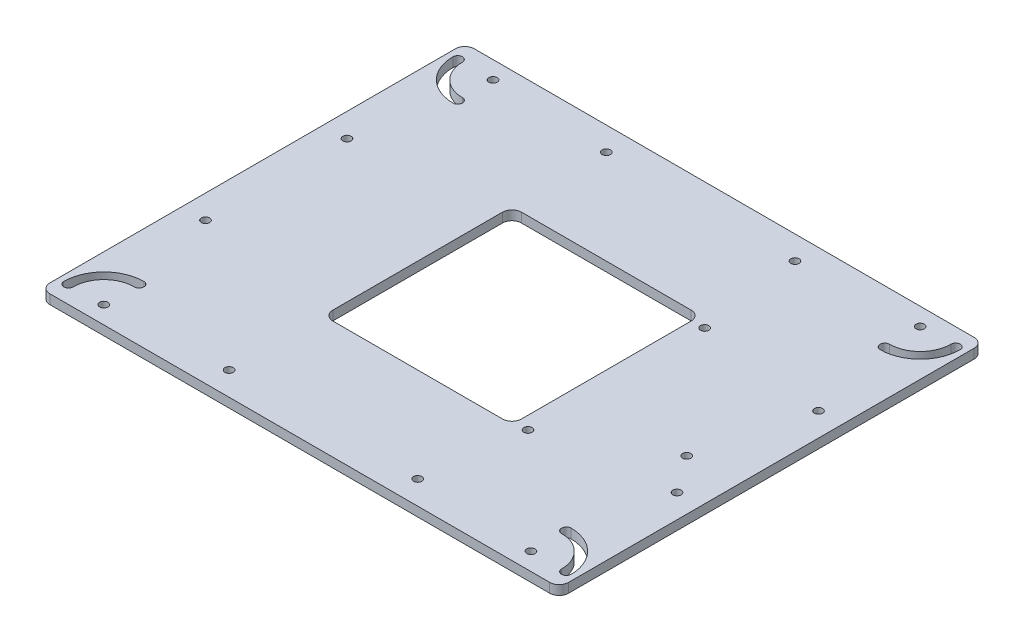
SolidWorks part; units mm, degrees
ref_plane "前视基准面" through (0, 0, 0) normal (0, 0, 1) x (1, 0, 0)
ref_plane "上视基准面" through (0, 0, 0) normal (0, 1, 0) x (1, 0, 0)
ref_plane "右视基准面" through (0, 0, 0) normal (1, 0, 0) x (0, 0, -1)
sketch "草图1" plane through (0, 0, 0) normal (0, 1, 0) x (1, 0, 0)
  line L1 (-110, -90) -> (110, -90)
  line L2 (-110, -90) -> (-110, 90)
  line L3 (-110, 90) -> (110, 90)
  line L4 (110, -90) -> (110, 90)
  line L5 (-110, -90) -> (110, 90) construction
  line L6 (-110, 90) -> (110, -90) construction
  point P0 (0, 0)
  dimension "D1" = 220
  dimension "D2" = 180
extrude "凸台-拉伸1" add sketch "草图1" along normal blind 4
sketch "草图2" plane through (0, 4, 0) normal (0, 1, 0) x (1, 0, 0)
  line L4 (110, -90) -> (110, 90)
  line L5 (110, 90) -> (-110, 90)
  line L6 (-110, 90) -> (-110, -90)
  line L7 (-110, -90) -> (110, -90)
  line L8 (110, -90) -> (110, 90)
  line L9 (110, 90) -> (-110, 90)
  line L10 (-110, 90) -> (-110, -90)
  line L11 (-110, -90) -> (110, -90)
  line L16 (-40, 40) -> (-40, -40)
  line L17 (-40, -40) -> (40, -40)
  line L18 (40, -40) -> (40, 40)
  line L19 (40, 40) -> (-40, 40)
  line L20 (-40, 40) -> (-40, -40)
  line L21 (-40, -40) -> (40, -40)
  line L22 (40, -40) -> (40, 40)
  line L23 (40, 40) -> (-40, 40)
  dimension "D1" = 0
  dimension "D2" = 10
extrude "切除-拉伸1" cut sketch "草图2" against normal blind 4 contours L20 L21 L22 L23
sketch "草图3" plane through (0, 0, 0) normal (0, -1, 0) x (-1, 0, 0)
  line L0 (123.6855, 0) -> (-123.4665, 0) construction
  line L1 (0, -98.0292) -> (0, 106.8372) construction
  circle A0 centre (90.5847, 82.5452) radius 1.75
  circle A1 centre (-90.5847, 82.5452) radius 1.75
  circle A2 centre (-90.5847, -82.5452) radius 1.75
  circle A3 centre (90.5847, -82.5452) radius 1.75
  arc A5 (90.5847, 65.5452) -> (107.5847, 82.5452) centre (90.5847, 82.5452) ccw
  arc A6 (90.5847, 69.5452) -> (103.5847, 82.5452) centre (90.5847, 82.5452) ccw
  arc A8 (107.5847, 82.5452) -> (103.5847, 82.5452) centre (105.5847, 82.5452) ccw
  arc A9 (90.5847, 69.5452) -> (90.5847, 65.5452) centre (90.5847, 67.5452) ccw
  arc A10 (90.5847, -69.5452) -> (90.5847, -65.5452) centre (90.5847, -67.5452) cw
  arc A11 (107.5847, -82.5452) -> (103.5847, -82.5452) centre (105.5847, -82.5452) cw
  arc A12 (90.5847, -69.5452) -> (103.5847, -82.5452) centre (90.5847, -82.5452) cw
  arc A13 (90.5847, -65.5452) -> (107.5847, -82.5452) centre (90.5847, -82.5452) cw
  circle A14 centre (90.5847, -82.5452) radius 1.75
  circle A15 centre (-90.5847, -82.5452) radius 1.75
  arc A16 (-90.5847, -65.5452) -> (-107.5847, -82.5452) centre (-90.5847, -82.5452) ccw
  arc A17 (-90.5847, -69.5452) -> (-103.5847, -82.5452) centre (-90.5847, -82.5452) ccw
  arc A18 (-107.5847, -82.5452) -> (-103.5847, -82.5452) centre (-105.5847, -82.5452) ccw
  arc A19 (-90.5847, -69.5452) -> (-90.5847, -65.5452) centre (-90.5847, -67.5452) ccw
  arc A20 (-90.5847, 69.5452) -> (-90.5847, 65.5452) centre (-90.5847, 67.5452) cw
  arc A21 (-107.5847, 82.5452) -> (-103.5847, 82.5452) centre (-105.5847, 82.5452) cw
  arc A22 (-90.5847, 69.5452) -> (-103.5847, 82.5452) centre (-90.5847, 82.5452) cw
  arc A23 (-90.5847, 65.5452) -> (-107.5847, 82.5452) centre (-90.5847, 82.5452) cw
  circle A24 centre (-90.5847, -82.5452) radius 1.75
  circle A25 centre (-90.5847, 82.5452) radius 1.75
  point P46 (0, 0)
extrude "切除-拉伸2" cut sketch "草图3" against normal blind 4 contours A6 A9 A5 A8 | A0 | A17 A19 A16 A18 | A2 | A23 A20 A22 A21 | A1 | A12 A11 A13 A10 | A3
sketch "草图5" plane through (0, 0, 0) normal (0, -1, 0) x (1, 0, 0)
  circle A0 centre (45.4012, 38.6263) radius 1.75
  circle A1 centre (88.5812, 14.4963) radius 1.75
  circle A2 centre (45.4012, -36.3037) radius 1.75
extrude "切除-拉伸3" cut sketch "草图5" against normal blind 4
sketch "草图6" plane through (0, 0, 0) normal (0, -1, 0) x (1, 0, 0)
  line L0 (-120.5811, 0) -> (119.4968, 0) construction
  line L1 (0, -99.411) -> (0, 101.0427) construction
  line L2 (110, -90) -> (-110, -90) construction
  line L3 (-110, -90) -> (-110, 90) construction
  circle A0 centre (-40, -80) radius 1.75
  circle A1 centre (-100, -30) radius 1.75
  circle A2 centre (40, -80) radius 1.75
  circle A3 centre (100, -30) radius 1.75
  circle A4 centre (100, 30) radius 1.75
  circle A5 centre (40, 80) radius 1.75
  circle A6 centre (-40, 80) radius 1.75
  circle A7 centre (-100, 30) radius 1.75
  point P11 (-101.0006, -12.6207)
  dimension "D1" = 40
  dimension "D2" = 10
  dimension "D3" = 10
  dimension "D4" = 30
extrude "切除-拉伸4" cut sketch "草图6" against normal blind 4
fillet "圆角1" radius 4 4 edges at (110, 2, 90) (110, 2, -90) (-110, 2, -90) (-110, 2, 90)
fillet "圆角2" radius 4 4 edges at (-40, 2, 40) (40, 2, 40) (-40, 2, -40) (40, 2, -40)
